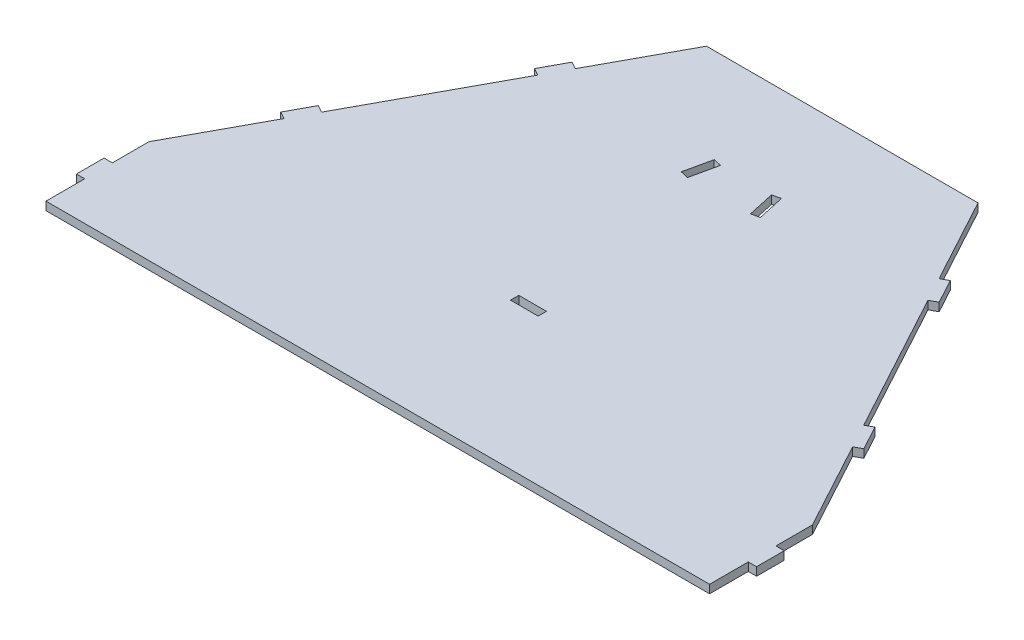
SolidWorks part; units mm, degrees
ref_plane "Front Plane" through (0, 0, 0) normal (0, 0, 1) x (1, 0, 0)
ref_plane "Top Plane" through (0, 0, 0) normal (0, 1, 0) x (1, 0, 0)
ref_plane "Right Plane" through (0, 0, 0) normal (1, 0, 0) x (0, 0, -1)
sketch "Sketch1" plane through (0, 0, 0) normal (0, 1, 0) x (1, 0, 0)
  line L23 (-123, 0) -> (123, 0)
  line L24 (-123, 0) -> (-123, 38)
  line L26 (123, 0) -> (123, 38)
  line L30 (-52.5, 168) -> (52.5, 168)
  line L32 (-52.5, 168) -> (-123, 38)
  line L33 (52.5, 168) -> (123, 38)
  point P2 (0, 0)
  dimension "D1" = 246
  dimension "D2" = 38
  dimension "D3" = 130
  dimension "D4" = 105
  dimension "D5" = 147.8859
  dimension "D6" = 147.8859
extrude "Boss-Extrude1" add sketch "Sketch1" along normal blind 3
sketch "Sketch2" plane through (0, 3, 0) normal (0, 1, 0) x (1, 0, 0)
  line L2 (-5, 53) -> (5, 53)
  line L7 (-123, 0) -> (-120, 0)
  line L14 (-5, 56) -> (-5, 53)
  line L17 (-5, 56) -> (5, 56)
  line L18 (5, 56) -> (5, 53)
  line L19 (12.1497, 133.83) -> (14.3145, 124.0671)
  line L20 (12.1497, 133.83) -> (9.2208, 133.1805)
  line L22 (9.2208, 133.1805) -> (11.3857, 123.4176)
  line L25 (-12.1497, 133.83) -> (-9.2208, 133.1805)
  line L26 (-12.1497, 133.83) -> (-14.3145, 124.0671)
  line L29 (-65.7724, 137.233) -> (-68.4096, 138.6632)
  line L30 (-70.5396, 128.4425) -> (-73.1768, 129.8726)
  line L31 (-105.4567, 70.3493) -> (-102.8196, 68.9191)
  line L32 (-100.6896, 79.1398) -> (-98.0524, 77.7097)
  line L34 (-120, 24) -> (-123, 24)
  line L36 (-120, 14) -> (-123, 14)
  line L37 (-70.5396, 128.4425) -> (-98.0524, 77.7097)
  line L38 (-120, 37.2389) -> (-120, 3)
  line L39 (-120, 3) -> (120, 3)
  line L40 (120, 3) -> (120, 37.2389)
  line L41 (120, 37.2389) -> (50.7142, 165)
  line L42 (50.7142, 165) -> (-50.7142, 165)
  line L43 (-50.7142, 165) -> (-120, 37.2389)
  line L44 (-120, 37.2389) -> (-120, 24)
  line L50 (-102.8196, 68.9191) -> (-120, 37.2389)
  line L51 (-120, 14) -> (-120, 0)
  line L66 (-65.7724, 137.233) -> (-49.0872, 168)
  line L71 (-49.0872, 168) -> (-52.5, 168)
  line L72 (-52.5, 168) -> (-68.4096, 138.6632)
  line L73 (-123, 38) -> (-123, 24)
  line L77 (-49.0872, 168) -> (-65.7724, 137.233)
  line L78 (-120, 37.2389) -> (-120, 24)
  line L88 (-120, 14) -> (-120, 0)
  line L89 (-123, 14) -> (-123, 0)
  line L90 (-102.8196, 68.9191) -> (-120, 37.2389)
  line L91 (-105.4567, 70.3493) -> (-123, 38)
  line L92 (-70.5396, 128.4425) -> (-98.0524, 77.7097)
  line L93 (-73.1768, 129.8726) -> (-100.6896, 79.1398)
  line L94 (-9.2208, 133.1805) -> (-11.3857, 123.4176)
  line L95 (73.1768, 129.8726) -> (100.6896, 79.1398)
  line L96 (70.5396, 128.4425) -> (98.0524, 77.7097)
  line L97 (105.4567, 70.3493) -> (123, 38)
  line L98 (102.8196, 68.9191) -> (120, 37.2389)
  line L99 (123, 14) -> (123, 0)
  line L100 (120, 14) -> (120, 0)
  line L101 (120, 37.2389) -> (120, 24)
  line L102 (49.0872, 168) -> (65.7724, 137.233)
  line L103 (-14.3145, 124.0671) -> (-11.3857, 123.4176)
  line L104 (14.3145, 124.0671) -> (11.3857, 123.4176)
  line L105 (123, 38) -> (123, 24)
  line L112 (52.5, 168) -> (68.4096, 138.6632)
  line L113 (49.0872, 168) -> (52.5, 168)
  line L114 (65.7724, 137.233) -> (49.0872, 168)
  line L115 (120, 14) -> (120, 0)
  line L116 (102.8196, 68.9191) -> (120, 37.2389)
  line L117 (120, 37.2389) -> (120, 24)
  line L118 (70.5396, 128.4425) -> (98.0524, 77.7097)
  line L119 (120, 14) -> (123, 14)
  line L121 (120, 24) -> (123, 24)
  line L123 (100.6896, 79.1398) -> (98.0524, 77.7097)
  line L124 (105.4567, 70.3493) -> (102.8196, 68.9191)
  line L125 (70.5396, 128.4425) -> (73.1768, 129.8726)
  line L126 (65.7724, 137.233) -> (68.4096, 138.6632)
  line L127 (123, 0) -> (120, 0)
  point P4 (-30, 56)
  point P6 (30, 56)
  point P10 (0, 53)
  line M62 (-123, 38) -> (-123, 0)
  line M63 (-123, 0) -> (123, 0)
  line M64 (123, 0) -> (123, 38)
  line M65 (123, 38) -> (52.5, 168)
  line M66 (52.5, 168) -> (-52.5, 168)
  line M67 (-52.5, 168) -> (-123, 38)
  dimension "D1" = 3
  dimension "D2" = 3
  dimension "D3" = 35
  dimension "D5" = 3
  dimension "D4" = 10
  dimension "D6" = 10
  dimension "D7" = 10
  dimension "D8" = 36.8
  dimension "D9" = 10
  dimension "D10" = 3
  dimension "D11" = 14
  dimension "D12" = 10
  dimension "D13" = 10
  dimension "D14" = 14
  dimension "D24" = 3
  dimension "D25" = 3
  dimension "D26" = 3
  dimension "D27" = 3
extrude "Cut-Extrude3" cut sketch "Sketch2" against normal blind 10 contours L119 L100 M63 M64 | L124 L98 L101 L121 M65 M64 | L125 L96 L123 M65 | L102 L126 M65 M66 | L104 L19 L20 L22 | L26 L103 L94 L25 | L18 L17 L14 L2 | L29 L66 M66 M67 | L37 L30 L32 M67 | L51 L36 M62 M63 | L50 L31 L34 L44 M67 M62
